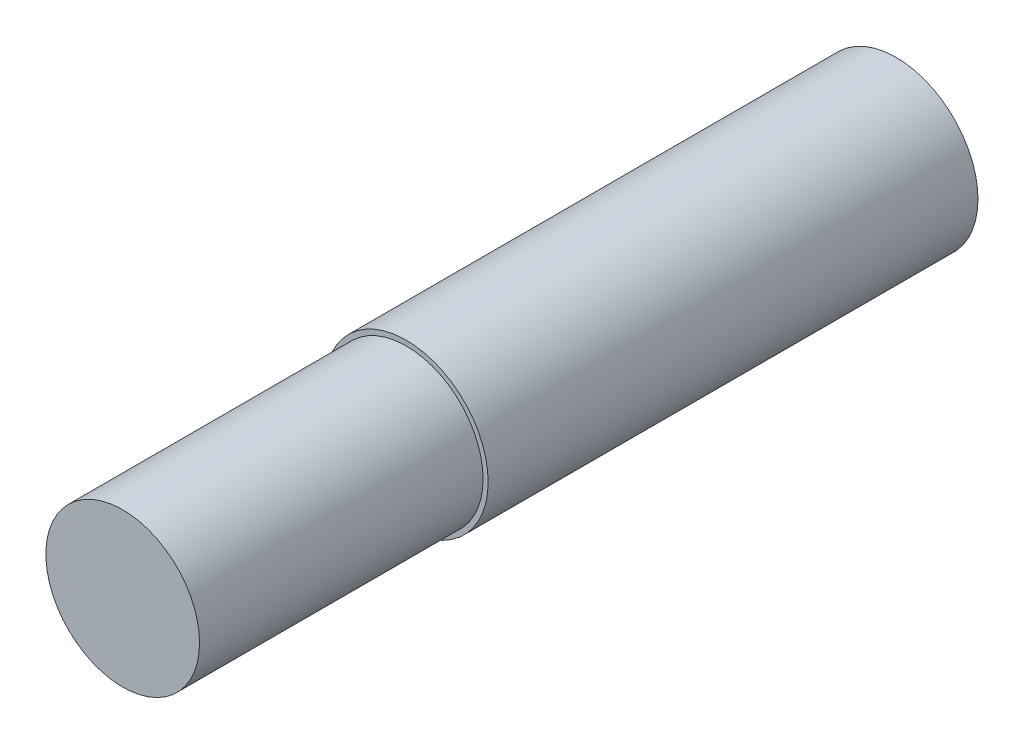
SolidWorks part; units mm, degrees
ref_plane "Front Plane" through (0, 0, 0) normal (0, 0, 1) x (1, 0, 0)
ref_plane "Top Plane" through (0, 0, 0) normal (0, 1, 0) x (1, 0, 0)
ref_plane "Right Plane" through (0, 0, 0) normal (1, 0, 0) x (0, 0, -1)
sketch "Sketch1" plane through (0, 0, 0) normal (0, 0, 1) x (1, 0, 0)
  circle A0 centre (0, 0) radius 3.175
  dimension "D1" = 6.35
extrude "Boss-Extrude1" add sketch "Sketch1" along normal blind 19
sketch "Sketch2" plane through (0, 0, 19) normal (0, 0, 1) x (1, 0, 0)
  circle A0 centre (0, 0) radius 2.98
  dimension "D1" = 5.96
extrude "Boss-Extrude2" add sketch "Sketch2" along normal blind 11
